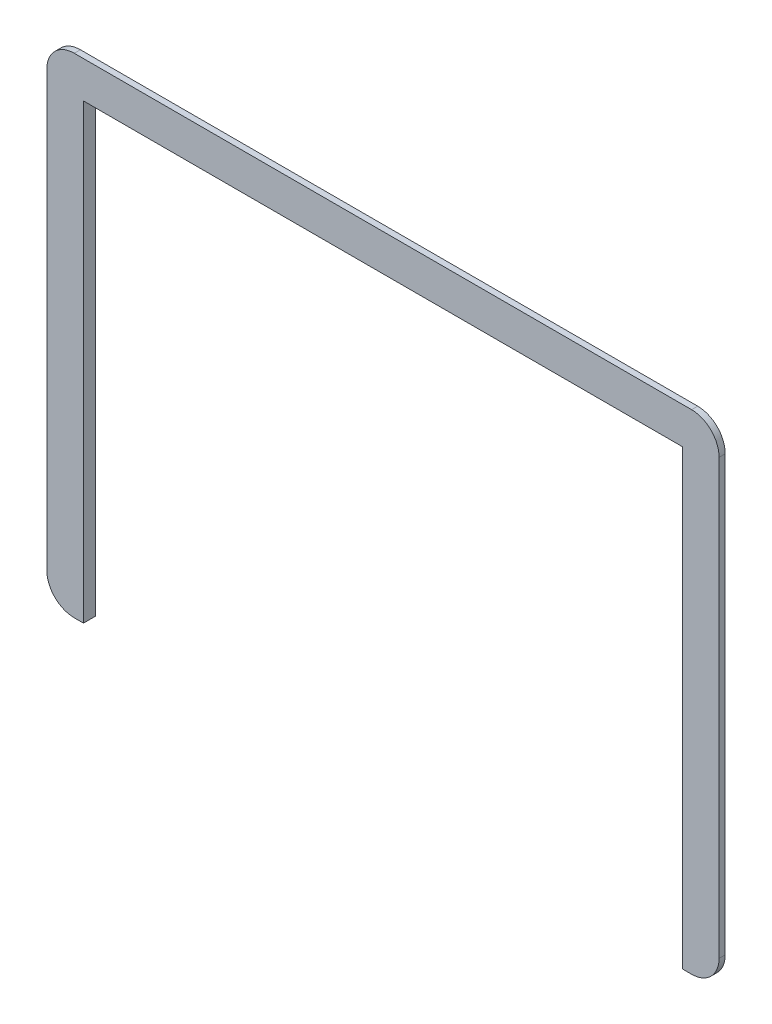
SolidWorks part; units mm, degrees
ref_plane "Plan de face" through (0, 0, 0) normal (0, 0, 1) x (1, 0, 0)
ref_plane "Plan de dessus" through (0, 0, 0) normal (0, 1, 0) x (1, 0, 0)
ref_plane "Plan de droite" through (0, 0, 0) normal (1, 0, 0) x (0, 0, -1)
sketch "Esquisse1" plane through (0, 0, 0) normal (0, 0, 1) x (1, 0, 0)
  line L0 (-40.7055, -19.8684) -> (-30.7055, -19.8684)
  line L1 (-30.7055, -19.8684) -> (-30.7055, 130.1316)
  line L2 (-30.7055, 130.1316) -> (169.2945, 130.1316)
  line L3 (169.2945, 130.1316) -> (169.2945, -19.8684)
  line L4 (169.2945, -19.8684) -> (179.2945, -19.8684)
  line L5 (179.2945, -19.8684) -> (179.2945, 140.1316)
  line L6 (179.2945, 140.1316) -> (-40.7055, 140.1316)
  line L7 (-40.7055, 140.1316) -> (-40.7055, -19.8684)
  dimension "D1" = 10
  dimension "D2" = 10
  dimension "D3" = 10
  dimension "D4" = 150
  dimension "D5" = 150
  dimension "D6" = 200
extrude "Boss.-Extru.1" add sketch "Esquisse1" along normal blind 2
sketch "Esquisse2" plane through (0, 0, 0) normal (0, 0, 1) x (1, 0, 0)
  line L0 (-30.7055, -19.8684) -> (-28.7055, -19.8684)
  line L1 (-28.7055, -19.8684) -> (-28.7055, 128.1316)
  line L2 (-28.7055, 128.1316) -> (167.2945, 128.1316)
  line L3 (167.2945, 128.1316) -> (167.2945, -19.8684)
  line L4 (167.2945, -19.8684) -> (169.2945, -19.8684)
  line L5 (169.2945, -19.8684) -> (169.2945, 130.1316)
  line L6 (169.2945, 130.1316) -> (169.2945, -19.8684) construction
  line L7 (-30.7055, 130.1316) -> (169.2945, 130.1316) construction
  line L8 (169.2945, 130.1316) -> (-30.7055, 130.1316)
  line L9 (-30.7055, 130.1316) -> (-30.7055, -19.8684)
  dimension "D1" = 2
  dimension "D2" = 2
  dimension "D3" = 2
extrude "Boss.-Extru.2" add sketch "Esquisse2" against normal blind 4 from vertex at 2 starting at point (-30.7055, -19.8684, 2)
sketch "Esquisse3" plane through (0, 0, 0) normal (0, 0, 1) x (1, 0, 0)
fillet "Congé1" radius 9 4 edges at (179.2945, -19.8684, 1) (179.2945, 140.1316, 1) (-40.7055, 140.1316, 1) (-40.7055, -19.8684, 1)
